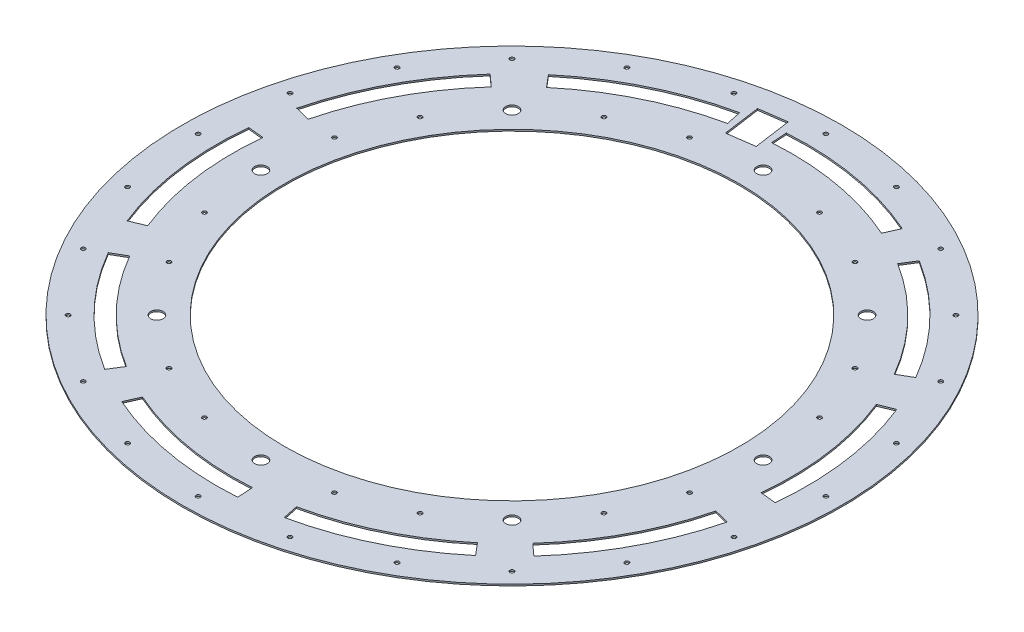
SolidWorks part; units mm, degrees
ref_plane "Front Plane" through (0, 0, 0) normal (0, 0, 1) x (1, 0, 0)
ref_plane "Top Plane" through (0, 0, 0) normal (0, 1, 0) x (1, 0, 0)
ref_plane "Right Plane" through (0, 0, 0) normal (1, 0, 0) x (0, 0, -1)
sketch "Sketch1" plane through (0, 0, 0) normal (0, 1, 0) x (1, 0, 0)
  line L0 (0, -1000) -> (0, 49000) construction
  line L1 (-1000, 0) -> (49000, 0) construction
  line L2 (0, 0) -> (-231.8222, 62.1166) construction
  line L3 (-231.8222, 62.1166) -> (-289.7777, 77.6457) construction
  line L4 (0, 0) -> (-41.7519, 297.0804) construction
  line L5 (-53.6512, 288.3393) -> (-27.9042, 291.9578)
  line L6 (-27.9042, 291.9578) -> (-22.894, 256.3081)
  line L7 (-22.894, 256.3081) -> (-48.641, 252.6896)
  line L8 (-48.641, 252.6896) -> (-53.6512, 288.3393)
  line L9 (-48.641, 252.6896) -> (-27.9042, 291.9578) construction
  line L10 (-53.6512, 288.3393) -> (-22.894, 256.3081) construction
  line L11 (-19.7086, 281.8462) -> (-18.6599, 266.8484)
  line L13 (108.8021, 244.3734) -> (114.9171, 258.108)
  line L14 (0, 0) -> (114.9171, 258.108) construction
  line L15 (231.6618, 133.75) -> (244.682, 141.2672)
  line L16 (149.7204, 239.6028) -> (141.7534, 226.8529)
  line L17 (266.0346, -27.9614) -> (280.9866, -29.5329)
  line L18 (261.9613, 105.8392) -> (248.0217, 100.2073)
  line L19 (198.7912, -178.9924) -> (209.964, -189.0524)
  line L20 (274.1419, -68.3513) -> (259.5541, -64.7141)
  line L21 (55.6164, -261.6545) -> (58.7422, -276.3603)
  line L22 (181.6096, -216.4339) -> (171.9457, -204.9169)
  line L23 (-108.8021, -244.3734) -> (-114.9171, -258.108)
  line L24 (19.7086, -281.8462) -> (18.6599, -266.8484)
  line L25 (-231.6618, -133.75) -> (-244.682, -141.2672)
  line L26 (-149.7204, -239.6028) -> (-141.7534, -226.8529)
  line L27 (-266.0346, 27.9614) -> (-280.9866, 29.5329)
  line L28 (-261.9613, -105.8392) -> (-248.0217, -100.2073)
  line L29 (-198.7912, 178.9924) -> (-209.964, 189.0524)
  line L30 (-274.1419, 68.3513) -> (-259.5541, 64.7141)
  line L31 (-55.6164, 261.6545) -> (-58.7422, 276.3603)
  line L32 (-181.6096, 216.4339) -> (-171.9457, 204.9169)
  circle A0 centre (0, 0) radius 315
  circle A1 centre (0, 0) radius 217.5
  circle A2 centre (0, 240) radius 6
  circle A3 centre (169.7056, 169.7056) radius 6
  circle A4 centre (240, 0) radius 6
  circle A5 centre (169.7056, -169.7056) radius 6
  circle A6 centre (0, -240) radius 6
  circle A7 centre (-169.7056, -169.7056) radius 6
  circle A8 centre (-240, 0) radius 6
  circle A9 centre (-169.7056, 169.7056) radius 6
  circle A10 centre (0, 0) radius 240 construction
  circle A11 centre (-231.8222, 62.1166) radius 2
  circle A12 centre (-207.8461, 120.0003) radius 2
  circle A14 centre (-119.9997, 207.8468) radius 2
  circle A15 centre (-62.1161, 231.8231) radius 2
  circle A17 centre (62.1176, 231.8232) radius 2
  circle A18 centre (120.0013, 207.8471) radius 2
  circle A20 centre (207.8478, 120.0007) radius 2
  circle A21 centre (231.8241, 62.1171) radius 2
  circle A23 centre (231.8242, -62.1166) radius 2
  circle A24 centre (207.8481, -120.0003) radius 2
  circle A26 centre (120.0017, -207.8468) radius 2
  circle A27 centre (62.1181, -231.8231) radius 2
  circle A29 centre (-62.1156, -231.8232) radius 2
  circle A30 centre (-119.9993, -207.8471) radius 2
  circle A32 centre (-207.8458, -120.0007) radius 2
  circle A33 centre (-231.8221, -62.1171) radius 2
  arc A35 (-168.2848, -171.1146) -> (-171.1133, -168.2862) centre (-169.7051, -169.7065) ccw [skipped]
  arc A36 (-1.9987, -239.9917) -> (0, -242.001) centre (0.0013, -240.001) ccw [skipped]
  arc A37 (168.2862, -171.1133) -> (171.1146, -168.2849) centre (169.7075, -169.7061) ccw [skipped]
  arc A38 (238.002, 0) -> (239.9917, -1.9997) centre (240.002, 0.0003) ccw [skipped]
  arc A39 (171.1142, 168.2852) -> (168.2859, 171.1136) centre (169.7071, 169.7065) ccw [skipped]
  arc A40 (-1.9992, 239.9917) -> (-1.4433, 238.6172) centre (0.0007, 240.001) ccw [skipped]
  arc A41 (-168.2852, 171.1142) -> (-171.1136, 168.2859) centre (-169.7055, 169.7061) ccw [skipped]
  arc A42 (-239.9917, -2.0002) -> (-238, 0) centre (-240, -0.0003) ccw [skipped]
  circle A43 centre (0, 0) radius 300 construction
  circle A44 centre (-289.7777, 77.6457) radius 2
  circle A45 centre (-259.8076, 150) radius 2
  circle A46 centre (-212.132, 212.132) radius 2
  circle A47 centre (-150, 259.8076) radius 2
  circle A48 centre (-77.6457, 289.7777) radius 2
  circle A49 centre (0, 300) radius 2
  circle A50 centre (77.6457, 289.7777) radius 2
  circle A51 centre (150, 259.8076) radius 2
  circle A52 centre (212.132, 212.132) radius 2
  circle A53 centre (259.8076, 150) radius 2
  circle A54 centre (289.7777, 77.6457) radius 2
  circle A55 centre (300, 0) radius 2
  circle A56 centre (289.7777, -77.6457) radius 2
  circle A57 centre (259.8076, -150) radius 2
  circle A58 centre (212.132, -212.132) radius 2
  circle A59 centre (150, -259.8076) radius 2
  circle A60 centre (77.6457, -289.7777) radius 2
  circle A61 centre (0, -300) radius 2
  circle A62 centre (-77.6457, -289.7777) radius 2
  circle A63 centre (-150, -259.8076) radius 2
  circle A64 centre (-212.132, -212.132) radius 2
  circle A65 centre (-259.8076, -150) radius 2
  circle A66 centre (-289.7777, -77.6457) radius 2
  circle A67 centre (-300, 0) radius 2
  circle A68 centre (0, 0) radius 275 construction
  circle A71 centre (0, 0) radius 282.5344 construction
  circle A72 centre (0, 0) radius 267.5 construction
  arc A74 (-19.7086, 281.8462) -> (114.9171, 258.108) centre (0, 0) cw
  arc A75 (-18.6599, 266.8484) -> (108.8021, 244.3734) centre (0, 0) cw
  arc A76 (149.7204, 239.6028) -> (244.682, 141.2672) centre (0, 0) cw
  arc A77 (141.7534, 226.8529) -> (231.6618, 133.75) centre (0, 0) cw
  arc A78 (261.9613, 105.8392) -> (280.9866, -29.5329) centre (0, 0) cw
  arc A79 (248.0217, 100.2073) -> (266.0346, -27.9614) centre (0, 0) cw
  arc A80 (274.1419, -68.3513) -> (209.964, -189.0524) centre (0, 0) cw
  arc A81 (259.5541, -64.7141) -> (198.7912, -178.9924) centre (0, 0) cw
  arc A82 (181.6096, -216.4339) -> (58.7422, -276.3603) centre (0, 0) cw
  arc A83 (171.9457, -204.9169) -> (55.6164, -261.6545) centre (0, 0) cw
  arc A84 (19.7086, -281.8462) -> (-114.9171, -258.108) centre (0, 0) cw
  arc A85 (18.6599, -266.8484) -> (-108.8021, -244.3734) centre (0, 0) cw
  arc A86 (-149.7204, -239.6028) -> (-244.682, -141.2672) centre (0, 0) cw
  arc A87 (-141.7534, -226.8529) -> (-231.6618, -133.75) centre (0, 0) cw
  arc A88 (-261.9613, -105.8392) -> (-280.9866, 29.5329) centre (0, 0) cw
  arc A89 (-248.0217, -100.2073) -> (-266.0346, 27.9614) centre (0, 0) cw
  arc A90 (-274.1419, 68.3513) -> (-209.964, 189.0524) centre (0, 0) cw
  arc A91 (-259.5541, 64.7141) -> (-198.7912, 178.9924) centre (0, 0) cw
  arc A92 (-181.6096, 216.4339) -> (-58.7422, 276.3603) centre (0, 0) cw
  arc A93 (-171.9457, 204.9169) -> (-55.6164, 261.6545) centre (0, 0) cw
  point P26 (0, 0)
  point P29 (0, 0)
  point P78 (0.001, 0)
  point P137 (0, 0)
  point P139 (-38.2726, 272.3237)
  point P190 (0, 0)
  dimension "D1" = 630
  dimension "D2" = 435
  dimension "D3" = 240
  dimension "D4" = 12
  dimension "D8" = 4
  dimension "D9" = 600
  dimension "D11" = 4
  dimension "D13" = 480
  dimension "D14" = 12
  dimension "D17" = 24
  dimension "D20" = 4
  dimension "D6" = 15
  dimension "D10" = 15
  dimension "D15" = 8
  dimension "D16" = 275
  dimension "D18" = 36
  dimension "D19" = 26
  dimension "D21" = 10
  dimension "D5" = 8
  dimension "D7" = 24
  dimension "D12" = 24
extrude "Boss-Extrude1" add sketch "Sketch1" along normal mid plane 1.5
